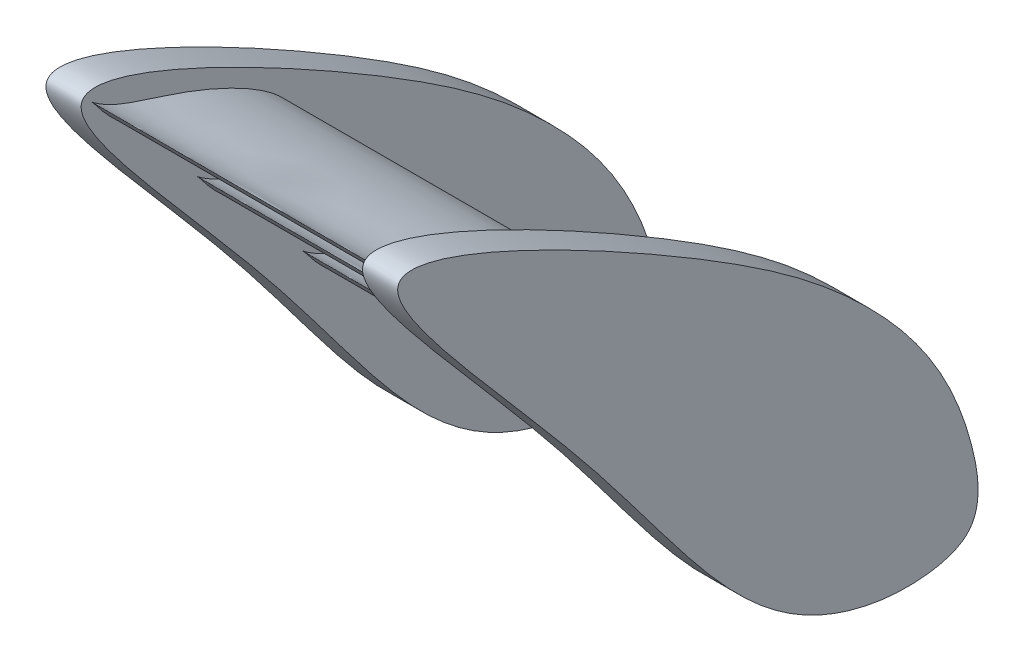
SolidWorks part; units mm, degrees
ref_plane "Front Plane" through (0, 0, 0) normal (0, 0, 1) x (1, 0, 0)
ref_plane "Top Plane" through (0, 0, 0) normal (0, 1, 0) x (1, 0, 0)
ref_plane "Right Plane" through (0, 0, 0) normal (1, 0, 0) x (0, 0, -1)
curve "Curve1"
  spline degree 3 poles (0, -3.9619, 2517.9534) (0, 1.1365, 2545.4425) (0, -4.9579, 2519.177) (0, -12.8325, 2499.6157) (0, -29.7367, 2455.056) (0, -50.9492, 2404.5871) (0, -74.8451, 2342.3392) (0, -97.9633, 2270.6258) (0, -119.945, 2188.7397) (0, -141.9229, 2097.7018) (0, -163.2451, 1998.422) (0, -183.4343, 1892.2112) (0, -201.855, 1780.2707) (0, -217.8125, 1663.6504) (0, -230.4614, 1543.2304) (0, -240.0919, 1420.1356) (0, -246.6331, 1295.4473) (0, -249.4289, 1170.3114) (0, -248.8898, 1045.8465) (0, -245.223, 923.267) (0, -238.484, 803.884) (0, -228.8083, 688.9746) (0, -216.2687, 579.7388) (0, -201.0526, 477.3131) (0, -183.2877, 382.7152) (0, -163.261, 296.8843) (0, -141.1714, 220.6095) (0, -117.4479, 154.5955) (0, -92.5016, 99.3974) (0, -66.9624, 55.503) (0, -42.2506, 24.222) (0, -23.6638, 8.6493) (0, -13.5157, 3.3444) (0, -9.7246, 1.6577) (0, -4.9047, 0.0811) (0, 1.145, -0.1316) (0, 6.198, 0.4438) (0, 19.0562, 3.0357) (0, 40.5675, 13.1361) (0, 69.0506, 37.0598) (0, 97.2338, 71.5516) (0, 124.0254, 116.4862) (0, 148.5733, 171.5364) (0, 170.2656, 236.5311) (0, 188.5313, 310.9924) (0, 203.0263, 394.5833) (0, 213.4332, 486.6355) (0, 219.6397, 586.6094) (0, 221.5681, 693.6356) (0, 219.2909, 806.9634) (0, 212.9543, 925.5218) (0, 202.783, 1048.3449) (0, 189.037, 1174.1602) (0, 172.0836, 1301.85) (0, 151.6407, 1430.1685) (0, 128.2571, 1558.5016) (0, 101.0045, 1686.111) (0, 73.1199, 1812.8178) (0, 46.247, 1937.4629) (0, 22.4147, 2058.1468) (0, 3.3618, 2172.5099) (0, -8.4515, 2276.7311) (0, -12.2191, 2367.8621) (0, -11.1296, 2438.1804) (0, -6.0096, 2494.8571) (0, -3.9619, 2517.9534) (0, 1.1365, 2545.4425) (0, -4.9579, 2519.177) knots -0.017889 -0.007931 -0.001977 0 0.00196 0.007574 0.016161 0.026998 0.039608 0.053884 0.070024 0.087907 0.107284 0.127909 0.149541 0.171956 0.195008 0.218564 0.242345 0.266186 0.289917 0.3133 0.336096 0.358081 0.379037 0.398774 0.417106 0.433898 0.449004 0.462356 0.473857 0.483498 0.491231 0.496511 0.497121 0.497754 0.498878 0.499984 0.501174 0.501773 0.507459 0.51443 0.522856 0.532728 0.544176 0.557155 0.571742 0.587847 0.605492 0.624533 0.644935 0.666504 0.689145 0.712615 0.736761 0.761297 0.786047 0.810836 0.835659 0.860436 0.884807 0.908351 0.930578 0.950848 0.968252 0.982111 0.992069 0.998023 1 1.00196 1.007574 1.016161 periodic
sketch "Sketch2" plane through (0, 0, 0) normal (1, 0, 0) x (0, 0, -1)
  line L0 (-2540, 0) -> (0, 0) construction
  line L1 (0, 0) -> (-2281.5646, 1317.2619) construction
  spline S1 degree 3 poles (-2182.5926, 1255.5456) (-2203.8496, 1273.7055) (-2184.1502, 1255.2948) (-2171.1469, 1238.6946) (-2141.0092, 1201.7753) (-2107.9081, 1158.1703) (-2065.9478, 1106.3518) (-2015.4012, 1050.4742) (-1955.4767, 990.4945) (-1887.6245, 925.942) (-1812.3067, 857.8366) (-1730.4202, 787.2468) (-1642.6872, 715.3238) (-1549.6698, 643.1941) (-1451.7074, 572.0297) (-1349.9195, 502.1421) (-1245.2068, 434.1331) (-1138.2339, 369.1439) (-1030.1746, 307.3784) (-922.1841, 249.2642) (-815.4259, 195.4088) (-711.0737, 146.3335) (-610.2029, 102.5752) (-513.8916, 64.5399) (-423.0849, 32.6258) (-338.7398, 7.054) (-261.6391, -11.9533) (-192.6076, -24.4151) (-132.3315, -30.41) (-81.5482, -30.2396) (-42.1021, -24.4791) (-19.3225, -16.1688) (-9.6542, -10.0328) (-6.2979, -7.5928) (-2.5226, -4.2071) (0.6865, 0.9258) (2.7147, 5.5896) (6.8991, 18.021) (8.9076, 41.7005) (2.4306, 78.3295) (-13.3486, 119.9828) (-38.8673, 165.6523) (-74.2682, 214.4364) (-119.7092, 265.7199) (-175.0616, 318.7691) (-240.206, 373.1176) (-314.7221, 428.1563) (-398.1989, 483.5182) (-489.922, 538.7014) (-589.2053, 593.3932) (-695.0482, 647.1847) (-806.5018, 699.7877) (-922.334, 750.791) (-1041.3934, 799.9537) (-1162.7419, 846.4089) (-1285.5735, 890.3247) (-1409.7127, 930.5279) (-1533.3864, 969.7326) (-1654.7686, 1008.7826) (-1771.2001, 1048.485) (-1879.7679, 1089.1663) (-1975.9327, 1131.0463) (-2056.7383, 1173.349) (-2117.091, 1209.4517) (-2163.6145, 1242.2241) (-2182.5926, 1255.5456) (-2203.8496, 1273.7055) (-2184.1502, 1255.2948) knots -0.017889 -0.007931 -0.001977 0 0.00196 0.007574 0.016161 0.026998 0.039608 0.053884 0.070024 0.087907 0.107284 0.127909 0.149541 0.171956 0.195008 0.218564 0.242345 0.266186 0.289917 0.3133 0.336096 0.358081 0.379037 0.398774 0.417106 0.433898 0.449004 0.462356 0.473857 0.483498 0.491231 0.496511 0.497121 0.497754 0.498878 0.499984 0.501174 0.501773 0.507459 0.51443 0.522856 0.532728 0.544176 0.557155 0.571742 0.587847 0.605492 0.624533 0.644935 0.666504 0.689145 0.712615 0.736761 0.761297 0.786047 0.810836 0.835659 0.860436 0.884807 0.908351 0.930578 0.950848 0.968252 0.982111 0.992069 0.998023 1 1.00196 1.007574 1.016161 only from (-2199.7045, 1270) to (-2199.7045, 1270)
  spline S2 degree 3 poles (-1039.5926, -14.4544) (-1060.8496, 3.7055) (-1041.1502, -14.7052) (-1028.1469, -31.3054) (-998.0092, -68.2247) (-964.9081, -111.8297) (-922.9478, -163.6482) (-872.4012, -219.5258) (-812.4767, -279.5055) (-744.6245, -344.058) (-669.3067, -412.1634) (-587.4202, -482.7532) (-499.6872, -554.6762) (-406.6698, -626.8059) (-308.7074, -697.9703) (-206.9195, -767.8579) (-102.2068, -835.8669) (4.7661, -900.8561) (112.8254, -962.6216) (220.8159, -1020.7358) (327.5741, -1074.5912) (431.9263, -1123.6665) (532.7971, -1167.4248) (629.1084, -1205.4601) (719.9151, -1237.3742) (804.2602, -1262.946) (881.3609, -1281.9533) (950.3924, -1294.4151) (1010.6685, -1300.41) (1061.4518, -1300.2396) (1100.8979, -1294.4791) (1123.6775, -1286.1688) (1133.3458, -1280.0328) (1136.7021, -1277.5928) (1140.4774, -1274.2071) (1143.6865, -1269.0742) (1145.7147, -1264.4104) (1149.8991, -1251.979) (1151.9076, -1228.2995) (1145.4306, -1191.6705) (1129.6514, -1150.0172) (1104.1327, -1104.3477) (1068.7318, -1055.5636) (1023.2908, -1004.2801) (967.9384, -951.2309) (902.794, -896.8824) (828.2779, -841.8437) (744.8011, -786.4818) (653.078, -731.2986) (553.7947, -676.6068) (447.9518, -622.8153) (336.4982, -570.2123) (220.666, -519.209) (101.6066, -470.0463) (-19.7419, -423.5911) (-142.5735, -379.6753) (-266.7127, -339.4721) (-390.3864, -300.2674) (-511.7686, -261.2174) (-628.2001, -221.515) (-736.7679, -180.8337) (-832.9327, -138.9537) (-913.7383, -96.651) (-974.091, -60.5483) (-1020.6145, -27.7759) (-1039.5926, -14.4544) (-1060.8496, 3.7055) (-1041.1502, -14.7052) knots -0.017889 -0.007931 -0.001977 0 0.00196 0.007574 0.016161 0.026998 0.039608 0.053884 0.070024 0.087907 0.107284 0.127909 0.149541 0.171956 0.195008 0.218564 0.242345 0.266186 0.289917 0.3133 0.336096 0.358081 0.379037 0.398774 0.417106 0.433898 0.449004 0.462356 0.473857 0.483498 0.491231 0.496511 0.497121 0.497754 0.498878 0.499984 0.501174 0.501773 0.507459 0.51443 0.522856 0.532728 0.544176 0.557155 0.571742 0.587847 0.605492 0.624533 0.644935 0.666504 0.689145 0.712615 0.736761 0.761297 0.786047 0.810836 0.835659 0.860436 0.884807 0.908351 0.930578 0.950848 0.968252 0.982111 0.992069 0.998023 1 1.00196 1.007574 1.016161 only from (-1056.7045, 0) to (-1056.7045, 0)
  spline S3 degree 3 poles (103.4074, -1284.4544) (82.1504, -1266.2945) (101.8498, -1284.7052) (114.8531, -1301.3054) (144.9908, -1338.2247) (178.0919, -1381.8297) (220.0522, -1433.6482) (270.5988, -1489.5258) (330.5233, -1549.5055) (398.3755, -1614.058) (473.6933, -1682.1634) (555.5798, -1752.7532) (643.3128, -1824.6762) (736.3302, -1896.8059) (834.2926, -1967.9703) (936.0805, -2037.8579) (1040.7932, -2105.8669) (1147.7661, -2170.8561) (1255.8254, -2232.6216) (1363.8159, -2290.7358) (1470.5741, -2344.5912) (1574.9263, -2393.6665) (1675.7971, -2437.4248) (1772.1084, -2475.4601) (1862.9151, -2507.3742) (1947.2602, -2532.946) (2024.3609, -2551.9533) (2093.3924, -2564.4151) (2153.6685, -2570.41) (2204.4518, -2570.2396) (2243.8979, -2564.4791) (2266.6775, -2556.1688) (2276.3458, -2550.0328) (2279.7021, -2547.5928) (2283.4774, -2544.2071) (2286.6865, -2539.0742) (2288.7147, -2534.4104) (2292.8991, -2521.979) (2294.9076, -2498.2995) (2288.4306, -2461.6705) (2272.6514, -2420.0172) (2247.1327, -2374.3477) (2211.7318, -2325.5636) (2166.2908, -2274.2801) (2110.9384, -2221.2309) (2045.794, -2166.8824) (1971.2779, -2111.8437) (1887.8011, -2056.4818) (1796.078, -2001.2986) (1696.7947, -1946.6068) (1590.9518, -1892.8153) (1479.4982, -1840.2123) (1363.666, -1789.209) (1244.6066, -1740.0463) (1123.2581, -1693.5911) (1000.4265, -1649.6753) (876.2873, -1609.4721) (752.6136, -1570.2674) (631.2314, -1531.2174) (514.7999, -1491.515) (406.2321, -1450.8337) (310.0673, -1408.9537) (229.2617, -1366.651) (168.909, -1330.5483) (122.3855, -1297.7759) (103.4074, -1284.4544) (82.1504, -1266.2945) (101.8498, -1284.7052) knots -0.017889 -0.007931 -0.001977 0 0.00196 0.007574 0.016161 0.026998 0.039608 0.053884 0.070024 0.087907 0.107284 0.127909 0.149541 0.171956 0.195008 0.218564 0.242345 0.266186 0.289917 0.3133 0.336096 0.358081 0.379037 0.398774 0.417106 0.433898 0.449004 0.462356 0.473857 0.483498 0.491231 0.496511 0.497121 0.497754 0.498878 0.499984 0.501174 0.501773 0.507459 0.51443 0.522856 0.532728 0.544176 0.557155 0.571742 0.587847 0.605492 0.624533 0.644935 0.666504 0.689145 0.712615 0.736761 0.761297 0.786047 0.810836 0.835659 0.860436 0.884807 0.908351 0.930578 0.950848 0.968252 0.982111 0.992069 0.998023 1 1.00196 1.007574 1.016161 only from (86.2955, -1270) to (86.2955, -1270)
  spline S4 degree 3 poles (1246.4074, -2554.4544) (1225.1504, -2536.2945) (1244.8498, -2554.7052) (1257.8531, -2571.3054) (1287.9908, -2608.2247) (1321.0919, -2651.8297) (1363.0522, -2703.6482) (1413.5988, -2759.5258) (1473.5233, -2819.5055) (1541.3755, -2884.058) (1616.6933, -2952.1634) (1698.5798, -3022.7532) (1786.3128, -3094.6762) (1879.3302, -3166.8059) (1977.2926, -3237.9703) (2079.0805, -3307.8579) (2183.7932, -3375.8669) (2290.7661, -3440.8561) (2398.8254, -3502.6216) (2506.8159, -3560.7358) (2613.5741, -3614.5912) (2717.9263, -3663.6665) (2818.7971, -3707.4248) (2915.1084, -3745.4601) (3005.9151, -3777.3742) (3090.2602, -3802.946) (3167.3609, -3821.9533) (3236.3924, -3834.4151) (3296.6685, -3840.41) (3347.4518, -3840.2396) (3386.8979, -3834.4791) (3409.6775, -3826.1688) (3419.3458, -3820.0328) (3422.7021, -3817.5928) (3426.4774, -3814.2071) (3429.6865, -3809.0742) (3431.7147, -3804.4104) (3435.8991, -3791.979) (3437.9076, -3768.2995) (3431.4306, -3731.6705) (3415.6514, -3690.0172) (3390.1327, -3644.3477) (3354.7318, -3595.5636) (3309.2908, -3544.2801) (3253.9384, -3491.2309) (3188.794, -3436.8824) (3114.2779, -3381.8437) (3030.8011, -3326.4818) (2939.078, -3271.2986) (2839.7947, -3216.6068) (2733.9518, -3162.8153) (2622.4982, -3110.2123) (2506.666, -3059.209) (2387.6066, -3010.0463) (2266.2581, -2963.5911) (2143.4265, -2919.6753) (2019.2873, -2879.4721) (1895.6136, -2840.2674) (1774.2314, -2801.2174) (1657.7999, -2761.515) (1549.2321, -2720.8337) (1453.0673, -2678.9537) (1372.2617, -2636.651) (1311.909, -2600.5483) (1265.3855, -2567.7759) (1246.4074, -2554.4544) (1225.1504, -2536.2945) (1244.8498, -2554.7052) knots -0.017889 -0.007931 -0.001977 0 0.00196 0.007574 0.016161 0.026998 0.039608 0.053884 0.070024 0.087907 0.107284 0.127909 0.149541 0.171956 0.195008 0.218564 0.242345 0.266186 0.289917 0.3133 0.336096 0.358081 0.379037 0.398774 0.417106 0.433898 0.449004 0.462356 0.473857 0.483498 0.491231 0.496511 0.497121 0.497754 0.498878 0.499984 0.501174 0.501773 0.507459 0.51443 0.522856 0.532728 0.544176 0.557155 0.571742 0.587847 0.605492 0.624533 0.644935 0.666504 0.689145 0.712615 0.736761 0.761297 0.786047 0.810836 0.835659 0.860436 0.884807 0.908351 0.930578 0.950848 0.968252 0.982111 0.992069 0.998023 1 1.00196 1.007574 1.016161 only from (1229.2955, -2540) to (1229.2955, -2540)
  dimension "D1" = 30
extrude "Boss-Extrude1" add sketch "Sketch2" along normal blind 3048 contours S1 | S2 | S3 | S4
sketch "Sketch3" plane through (0, 0, 0) normal (1, 0, 0) x (0, 0, -1)
  spline S0 degree 3 poles (947.8422, 53.4873) (-3907.3824, 2556.3186) (360.3208, -1825.3435) (1546.5531, -4080.1887) (3277.9228, -4303.7547) (4060.8136, -4160.7162) (3859.4226, -2685.1391) (2844.4437, -1372.3017) (947.8422, 53.4873) (-3907.3824, 2556.3186) (360.3208, -1825.3435) knots -0.457738 -0.33086 -0.218433 0 0.195823 0.428979 0.462086 0.497558 0.542262 0.66914 0.781567 1 1.195823 1.428979 1.462086 only from (-2294.8066, 1336.9146) to (-2294.8066, 1336.9146)
extrude "Boss-Extrude2" add sketch "Sketch3" against normal blind 381
ref_plane "Plane1" through (3048, 0, 0) normal (1, 0, 0) x (0, 0, -1)
sketch "Sketch4" plane through (3048, 0, 0) normal (1, 0, 0) x (0, 0, -1)
  spline S0 degree 3 poles (947.8422, 53.4873) (-3907.3824, 2556.3186) (360.3208, -1825.3435) (1546.5531, -4080.1887) (3277.9228, -4303.7547) (4060.8136, -4160.7162) (3859.4226, -2685.1391) (2844.4437, -1372.3017) (947.8422, 53.4873) (-3907.3824, 2556.3186) (360.3208, -1825.3435) knots -0.457738 -0.33086 -0.218433 0 0.195823 0.428979 0.462086 0.497558 0.542262 0.66914 0.781567 1 1.195823 1.428979 1.462086 only from (-2294.8066, 1336.9146) to (-2294.8066, 1336.9146)
extrude "Boss-Extrude3" add sketch "Sketch4" along normal blind 381
